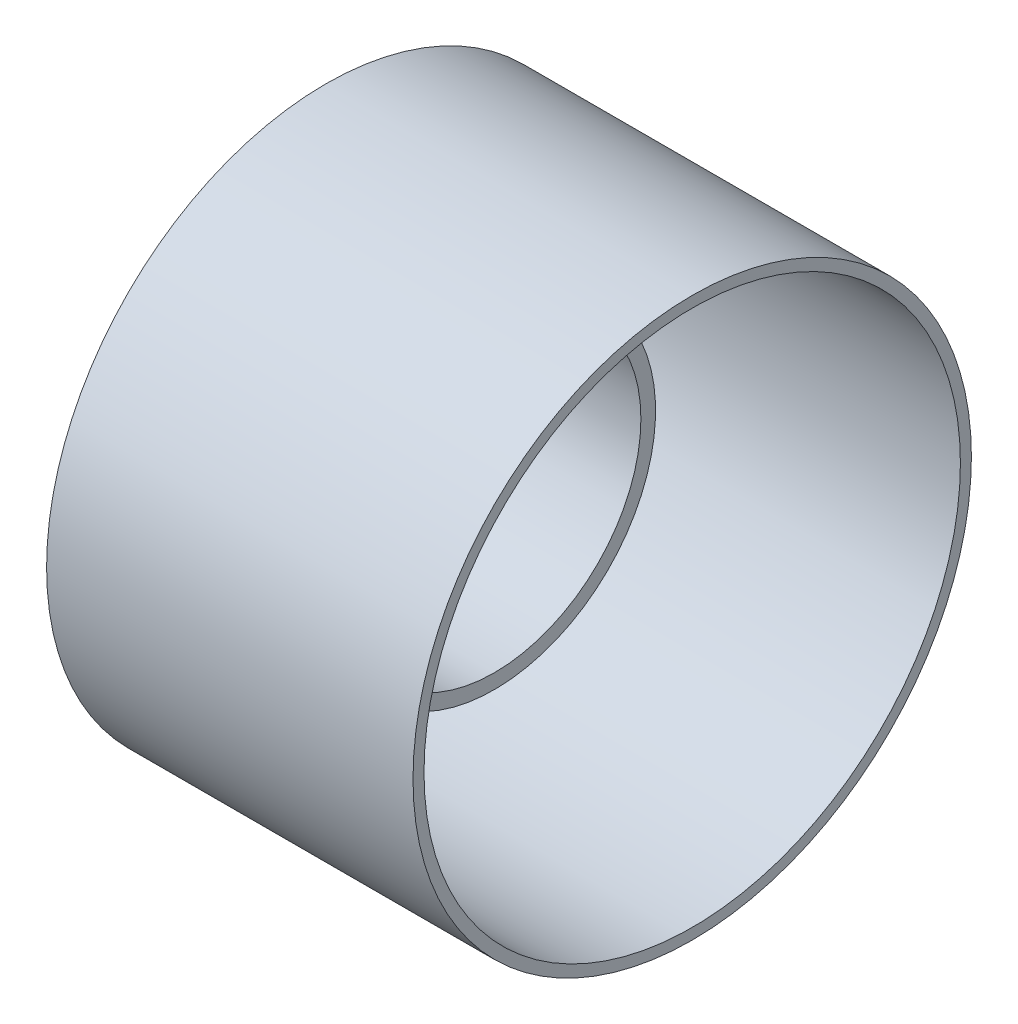
SolidWorks part; units mm, degrees
ref_plane "Front Plane" through (0, 0, 0) normal (0, 0, 1) x (1, 0, 0)
ref_plane "Top Plane" through (0, 0, 0) normal (0, 1, 0) x (1, 0, 0)
ref_plane "Right Plane" through (0, 0, 0) normal (1, 0, 0) x (0, 0, -1)
sketch "Sketch2" plane through (0, 0, 0) normal (0, 0, 1) x (1, 0, 0)
  line L0 (7.9001, 45.905) -> (46, 44)
  line L1 (0, 0) -> (6, 0) construction
  line L2 (0, 2) -> (0, 76.2)
  line L3 (0, 76.2) -> (6.2992, 76.2)
  line L4 (6, 2) -> (6, 38)
  line L5 (6.2992, 76.2) -> (100, 76.2)
  line L7 (8, 73.2) -> (100, 73.2)
  line L8 (100, 76.2) -> (100, 73.2)
  line L9 (8, 40) -> (46, 40)
  line L12 (46, 40) -> (46, 44)
  line L13 (6, 47.9025) -> (6, 71.2)
  line L14 (0, 2) -> (6, 2)
  line L15 (0, 2) -> (0, 0) construction
  arc A0 (6, 47.9025) -> (7.9001, 45.905) centre (8, 47.9025) ccw
  arc A1 (8, 40) -> (6, 38) centre (8, 38) ccw
  arc A2 (6, 71.2) -> (8, 73.2) centre (8, 71.2) cw
  point P9 (100, 74.7)
  point P15 (6, 46)
  dimension "D9" = 2
  dimension "D10" = 2
  dimension "D1" = 40
  dimension "D2" = 76.2
  dimension "D3" = 6
  dimension "D4" = 100
  dimension "D5" = 3
  dimension "D6" = 4
  dimension "D7" = 6
  dimension "D8" = 40
  dimension "D11" = 2
revolve "Revolve1" add sketch "Sketch2" angle 360 about L1
